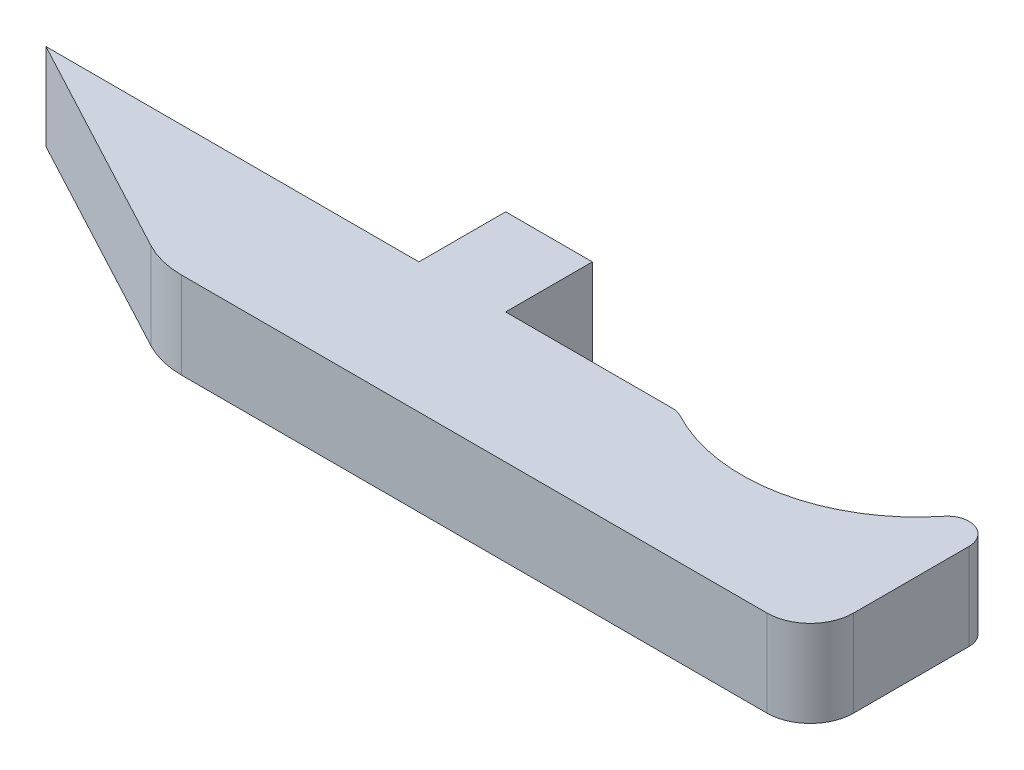
SolidWorks part; units mm, degrees
material "AISI 4130 Steel, annealed at 865C"
ref_plane "X-Y Datum" through (0, 0, 0) normal (0, 0, 1) x (1, 0, 0)
ref_plane "X-Z Datum" through (0, 0, 0) normal (0, 1, 0) x (1, 0, 0)
ref_plane "Y-Z Datum" through (0, 0, 0) normal (1, 0, 0) x (0, 0, -1)
sketch "Sketch1" plane through (0, 0, 0) normal (0, 1, 0) x (1, 0, 0)
  line L0 (58.9432, -34.753) -> (58.9432, -34.7341) construction
  line L1 (58.9432, -45.8687) -> (3.2156, -45.8687)
  line L2 (58.9432, -45.8687) -> (58.9432, -34.7435)
  line L3 (24.1452, -55.3937) -> (71.7702, -55.3937)
  line L4 (71.7702, -34.7435) -> (71.7702, -55.3937)
  line L5 (6.2845, -45.8687) -> (24.1452, -55.3937)
  line L8 (33.5895, -45.8687) -> (3.1095, -45.8687) construction
  line L9 (33.5895, -45.8687) -> (3.1095, -45.8687)
  circle A0 centre (58.9432, -34.7435) radius 12.827
  circle A1 centre (58.9432, -34.7435) radius 12.7
  circle A2 centre (58.9432, -34.7435) radius 12.7 construction
  dimension "D3" = 25.654
  dimension "D5" = 9.525
  dimension "D1" = 55.7276
  dimension "D2" = 11.1252
  dimension "D4" = 3.175
  dimension "D6" = 47.625
extrude "Boss-Extrude1" add sketch "Sketch1" along normal blind 6.35
fillet "Fillet1" radius 1.5875 2 edges at (52.5587, 3.175, 45.8687) (71.7702, 3.175, 34.7435)
fillet "Fillet2" radius 6.35 1 edges at (24.1452, 3.175, 55.3937)
fillet "Fillet3" radius 3.175 1 edges at (71.7702, 3.175, 55.3937)
sketch "Sketch2" plane through (0, 0, 45.8687) normal (0, 0, -1) x (-1, 0, 0)
  line L0 (-52.1488, 6.35) -> (-6.2845, 6.35) construction
  line L1 (-39.9395, 6.35) -> (-33.5895, 6.35)
  line L2 (-39.9395, 6.35) -> (-39.9395, 0)
  line L3 (-39.9395, 0) -> (-33.5895, 0)
  line L4 (-33.5895, 6.35) -> (-33.5895, 0)
  line L5 (-52.1488, 0) -> (-6.2845, 0) construction
  line L6 (-6.2845, 6.35) -> (-6.2845, 0) construction
  dimension "D1" = 27.305
  dimension "D2" = 6.35
extrude "Boss-Extrude2" add sketch "Sketch2" along normal blind 6.35
fillet "Fillet4" [suppressed] radius 0.7937
